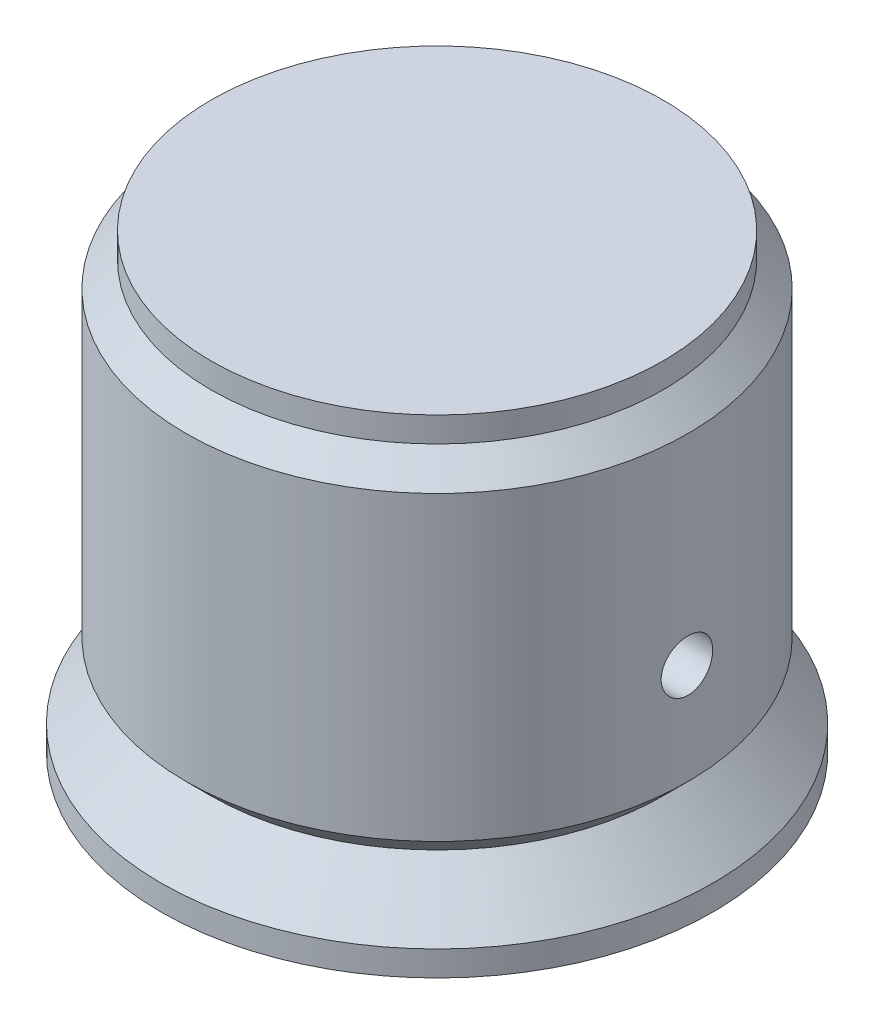
SolidWorks part; units mm, degrees
other "BODY"
ref_plane "Front Plane" through (0, 0, 0) normal (0, 0, 1) x (1, 0, 0)
ref_plane "Top Plane" through (0, 0, 0) normal (0, 1, 0) x (1, 0, 0)
ref_plane "Right Plane" through (0, 0, 0) normal (1, 0, 0) x (0, 0, -1)
sketch "Sketch1" plane through (0, 0, 0) normal (0, 0, 1) x (1, 0, 0)
  line L0 (0, 17.3589) -> (0, -1.4495) construction
  line L1 (7.1438, 14.2875) -> (7.1437, 13.4938)
  line L2 (7.1437, 13.4938) -> (7.9375, 12.7)
  line L3 (7.9375, 12.7) -> (7.9375, 3.175)
  line L4 (7.9375, 3.175) -> (7.1437, 2.3813)
  line L5 (7.1437, 2.3813) -> (8.7313, 0.7937)
  line L6 (8.7313, 0.7937) -> (8.7313, 0)
  line L7 (8.7313, 0) -> (0, 0)
  line L9 (9.6044, 0) -> (-9.6044, 0) construction
  line L10 (7.1438, 14.2875) -> (0, 14.2875)
  line L11 (0, 14.2875) -> (0, 0)
  dimension "D1" = 0.7937
  dimension "D3" = 15.875
  dimension "Length [X]" = 17.4625
  dimension "Length [X1]" = 14.2875
  dimension "D6" = 14.2875
  dimension "D7" = 45
  dimension "D8" = 9.525
  dimension "D9" = 1.5875
revolve "BODY" add sketch "Sketch1" angle 360 about L0
sketch "Sketch6" plane through (0, 0, 0) normal (0, 0, 1) x (1, 0, 0)
  line L0 (0, 13.9527) -> (0, -0.7095) construction
  line L1 (0, 13.4938) -> (1.2675, 12.762)
  line L2 (1.2675, 12.762) -> (1.2675, 12.4445)
  line L3 (1.2675, 12.4445) -> (1.585, 12.4445)
  line L4 (1.585, 12.4445) -> (1.585, 0.635)
  line L5 (-8.7313, 0) -> (8.7313, 0) construction
  line L6 (1.585, 0.635) -> (2.22, 0)
  line L7 (0, 13.4938) -> (0, 0)
  line L8 (0, 0) -> (2.22, 0)
  line L9 (7.1437, 13.4938) -> (-7.1437, 13.4938) construction
  dimension "D1" = 0.635
  dimension "D2" = 45
  dimension "D3" = 60
  dimension "D4" = 0.3175
  dimension "Bore [A]" = 3.1699
revolve "BORE-1" cut sketch "Sketch6" angle 360 about L0
sketch "Sketch2" plane through (0, 0, 0) normal (0, 0, 1) x (1, 0, 0)
  line L0 (-2.2488, 6.35) -> (9.3557, 6.35) construction
  line L1 (-8.7313, 0) -> (8.7313, 0) construction
  line L3 (0, 7.1641) -> (8.7313, 7.1641)
  line L4 (0, 7.1641) -> (0, 6.35)
  line L5 (0, 6.35) -> (8.7313, 6.35)
  line L6 (8.7313, 7.1641) -> (8.7313, 6.35)
  line L10 (8.7313, 0) -> (8.7313, 0.7937) construction
  dimension "Length [K]" = 6.35
  dimension "Set Screw DD1" = 1.6281
revolve "SET SCREW" cut sketch "Sketch2" angle 360 about L0
cosmetic thread "Cosmetic Thread1" parameters "Set Screw DD2"=2.1844
sketch "Sketch3" plane through (0, 0, 0) normal (1, 0, 0) x (0, 0, -1)
  line L0 (0, 6.35) -> (9.654, 6.35) construction
  line L1 (0, 7.8581) -> (0, -7.8581) construction
  line L2 (0, 6.35) -> (8.7313, 6.35)
  line L3 (0, 6.35) -> (0, 6.7208)
  line L4 (0, 6.7208) -> (8.7313, 6.7208)
  line L5 (8.7313, 6.35) -> (8.7313, 6.7208)
  line L6 (8.7313, 0) -> (8.7313, 0.7937) construction
  dimension "Length [X2]" = 0.7417
revolve "SUB DRILL" cut sketch "Sketch3" angle 360 about L0
